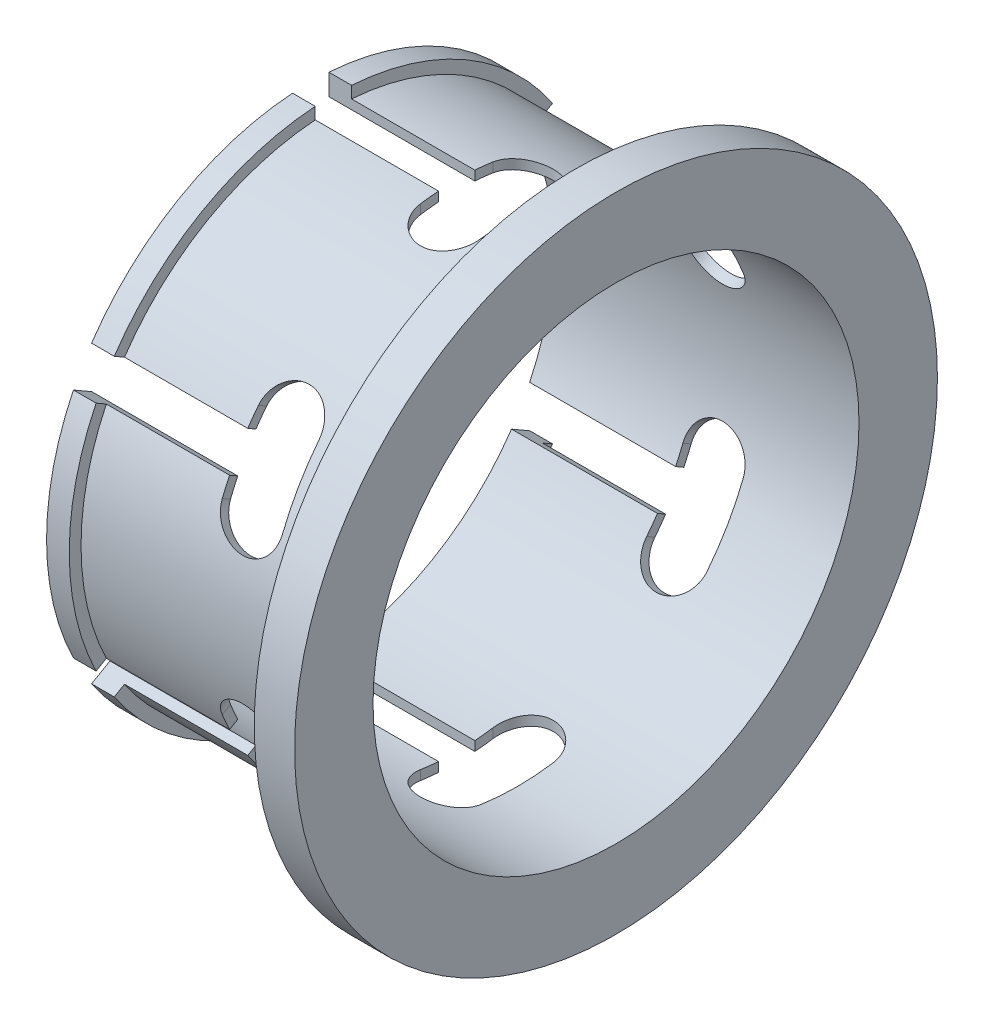
SolidWorks part; units mm, degrees
ref_plane "Front Plane" through (0, 0, 0) normal (0, 0, 1) x (1, 0, 0)
ref_plane "Top Plane" through (0, 0, 0) normal (0, 1, 0) x (1, 0, 0)
ref_plane "Right Plane" through (0, 0, 0) normal (1, 0, 0) x (0, 0, -1)
sketch "Sketch3" plane through (0, 0, 0) normal (0, 0, 1) x (1, 0, 0)
  line L0 (0, 0) -> (0, 76.454) construction
  line L1 (0, 76.454) -> (-12.7, 76.454)
  line L2 (0, 76.454) -> (0, 101.1339)
  line L3 (0, 101.1339) -> (-12.7, 101.1339)
  line L4 (-12.7, 101.1339) -> (-12.7, 79.4097)
  line L5 (-12.7, 79.4097) -> (-88.916, 79.4097)
  line L6 (-88.916, 79.4097) -> (-88.916, 83.114)
  line L7 (-88.916, 83.114) -> (-96.0567, 83.114)
  line L8 (-96.0567, 83.114) -> (-96.0567, 76.454)
  line L9 (-96.0567, 76.454) -> (-12.7, 76.454)
  line L10 (0, 0) -> (-96.0567, 0) construction
  dimension "D1" = 76.454
  dimension "D2" = 12.7
revolve "Revolve1" add sketch "Sketch3" angle 360 about L10
sketch "Sketch4" plane through (0, 0, 0) normal (0, 1, 0) x (1, 0, 0)
  line L0 (-96.0567, 5.715) -> (-96.0567, -5.715)
  line L1 (-96.0567, 83.114) -> (-96.0567, -83.114) construction
  line L2 (-96.0567, 83.114) -> (-96.0567, -83.114) construction
  line L3 (-96.0567, -5.715) -> (-50.1307, -5.715)
  line L4 (-96.0567, 5.715) -> (-50.1307, 5.715)
  line L6 (-40.6268, 11.3843) -> (-40.6268, -11.3843) construction
  line L7 (-31.1229, 11.3843) -> (-31.1229, -11.3843)
  line L8 (-50.1307, 11.3843) -> (-50.1307, 5.715)
  line L9 (-50.1307, -5.715) -> (-50.1307, -11.3843)
  arc A0 (-31.1229, 11.3843) -> (-50.1307, 11.3843) centre (-40.6268, 11.3843) ccw
  arc A1 (-50.1307, -11.3843) -> (-31.1229, -11.3843) centre (-40.6268, -11.3843) ccw
  point P0 (-53.1791, 111.8078)
  point P6 (-96.0567, 0)
  point P10 (-40.6268, 0)
  dimension "D1" = 11.43
extrude "Cut-Extrude1" cut sketch "Sketch4" against normal up to surface (82.3306 mm away) contours A0 L8 L4 L0 L3 L9 A1 L7
pattern_circular "CirPattern1" count 6 over 360 about axis through (0, 0, 0) along (1, 0, 0) of "Cut-Extrude1"
